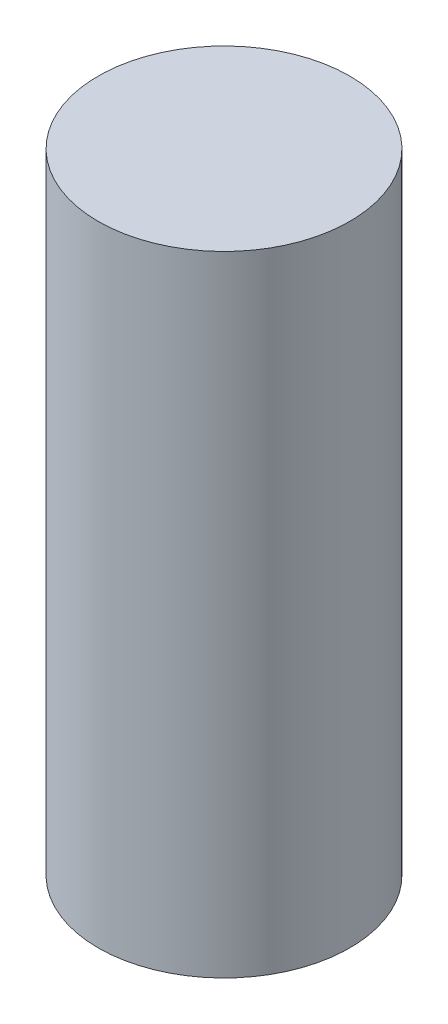
SolidWorks part; units mm, degrees
ref_plane "Front Plane" through (0, 0, 0) normal (0, 0, 1) x (1, 0, 0)
ref_plane "Top Plane" through (0, 0, 0) normal (0, 1, 0) x (1, 0, 0)
ref_plane "Right Plane" through (0, 0, 0) normal (1, 0, 0) x (0, 0, -1)
sketch "Sketch1" plane through (0, 0, 0) normal (0, 1, 0) x (1, 0, 0)
  circle A0 centre (0, 0) radius 2.4
  dimension "D1" = 4.8
extrude "Boss-Extrude1" add sketch "Sketch1" along normal blind 12
